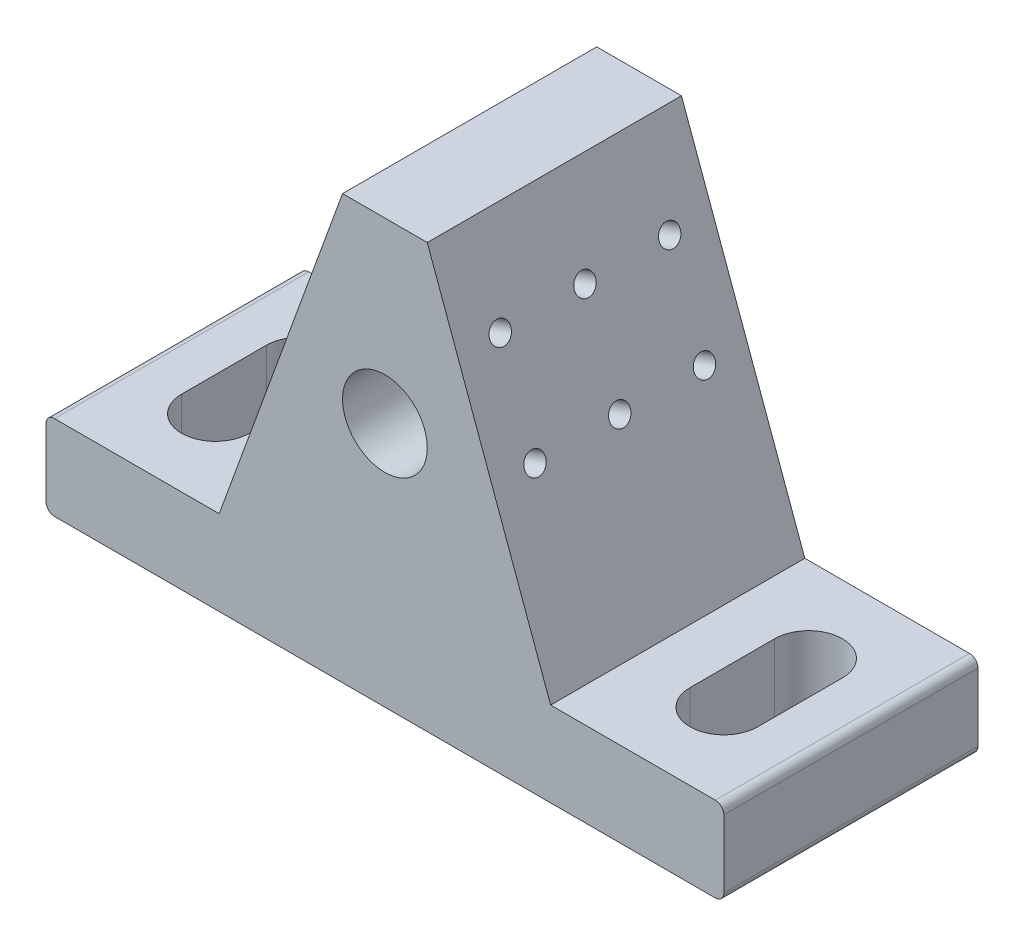
SolidWorks part; units mm, degrees
material "AISI 304"
ref_plane "Front Plane" through (0, 0, 0) normal (0, 0, 1) x (1, 0, 0)
ref_plane "Top Plane" through (0, 0, 0) normal (0, 1, 0) x (1, 0, 0)
ref_plane "Right Plane" through (0, 0, 0) normal (1, 0, 0) x (0, 0, -1)
sketch "Sketch2" plane through (0, 0, 0) normal (0, 0, 1) x (1, 0, 0)
  line L0 (0, 0) -> (0, 50) construction
  line L1 (-40, 0) -> (40, 0)
  line L2 (40, 0) -> (40, 10)
  line L3 (40, 10) -> (19.5588, 10)
  line L4 (19.5588, 10) -> (5, 50)
  line L5 (5, 50) -> (-5, 50)
  line L6 (-19.5588, 10) -> (-5, 50)
  line L7 (-40, 10) -> (-19.5588, 10)
  line L8 (-40, 0) -> (-40, 10)
  dimension "D1" = 10
  dimension "D2" = 10
  dimension "D3" = 110
  dimension "D4" = 80
  dimension "D5" = 50
extrude "Base Extrude" add sketch "Sketch2" along normal mid plane 30
sketch "Sketch4" plane through (0, 0, 0) normal (0, 1, 0) x (1, 0, 0)
  line L0 (30, -5) -> (30, 5) construction
  line L1 (26, -5) -> (26, 5)
  line L2 (34, -5) -> (34, 5)
  line L3 (40, 15) -> (19.5588, 15) construction
  arc A0 (26, -5) -> (34, -5) centre (30, -5) ccw
  arc A1 (34, 5) -> (26, 5) centre (30, 5) ccw
  point P2 (30, 0)
  dimension "D4" = 4
  dimension "D1" = 10
  dimension "D2" = 30
  dimension "D3" = 10
extrude "Slot Cut" cut sketch "Sketch4" along normal through all
mirror "Mirror1" about plane through (0, 0, 0) normal (1, 0, 0) of "Slot Cut"
sketch "Sketch5" plane through (0, 0, 15) normal (0, 0, 1) x (1, 0, 0)
  circle A0 centre (0, 29) radius 5
  dimension "D1" = 10
  dimension "D2" = 29
extrude "Guide Hole" cut sketch "Sketch5" against normal through all
hole_wizard "M3x0.5 Tapped Hole2" positions "3DSketch1" profile "Sketch10" tap size "M3x0.5" standard "ANSI Metric"
sketch3d "3DSketch1"
  line L0 (19.5588, 10, -15) -> (5, 50, -15) construction
  line L1 (19.5588, 10, 15) -> (19.5588, 10, -15) construction
  point P0 (12.7184, 28.7939, 10)
  dimension "D1" = 25
  dimension "D2" = 20
sketch "Sketch10" plane through (12.7184, 28.7939, 10) normal (0, 0, 1) x (-0.342, 0.9397, 0)
  line L0 (0, 0) -> (0, 8.2511)
  line L1 (0, 8.2511) -> (1.25, 7.5)
  line L2 (1.25, 7.5) -> (1.25, 0)
  line L5 (1.25, 0) -> (0, 0)
  line L10 (0, 8.2511) -> (-1.25, 7.5) construction
  line L11 (0, -6.35) -> (0, 107.95) construction
  dimension "Tap Drill Dia." = 2.5
  dimension "Tap Drill Depth" = 7.5
  dimension "Drill Angle" = 118
cosmetic thread "Hole Thread2" parameters "D1"=6, "D2"=3
pattern_linear "LPattern1" count 3 spacing 10 along (0, 0, -1) count 2 spacing 12 along (-0.342, 0.9397, 0) of "M3x0.5 Tapped Hole2"
cosmetic thread "Hole Thread3" parameters "D1"=6, "D2"=3
cosmetic thread "Hole Thread4" parameters "D1"=6, "D2"=3
cosmetic thread "Hole Thread5" parameters "D1"=6, "D2"=3
cosmetic thread "Hole Thread6" parameters "D1"=6, "D2"=3
cosmetic thread "Hole Thread7" parameters "D1"=6, "D2"=3
fillet "Fillet1" radius 1 4 edges at (-40, 0, 0) (40, 0, 0) (-40, 10, 0) (40, 10, 0)
